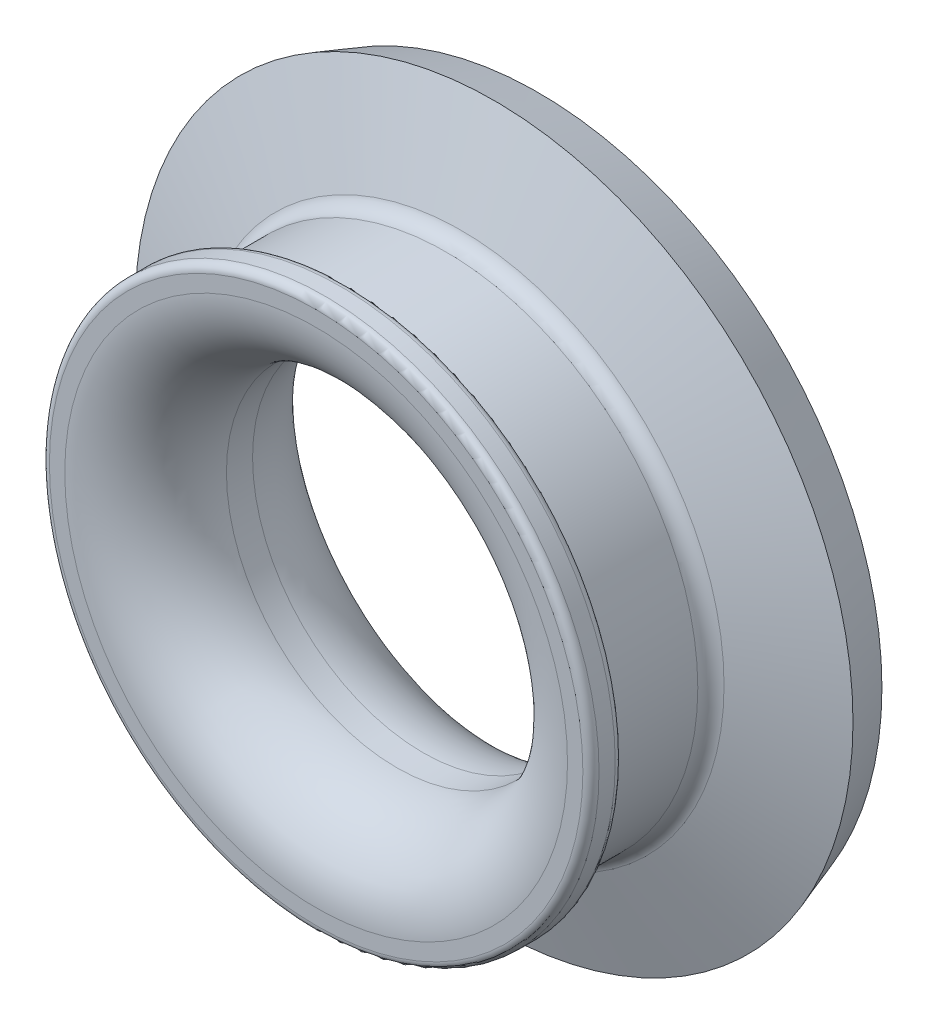
SolidWorks part; units mm, degrees
material "Nitrile Rubber"
ref_plane "Front Plane" through (0, 0, 0) normal (0, 0, 1) x (1, 0, 0)
ref_plane "Top Plane" through (0, 0, 0) normal (0, 1, 0) x (1, 0, 0)
ref_plane "Right Plane" through (0, 0, 0) normal (1, 0, 0) x (0, 0, -1)
sketch "Sketch1" plane through (0, 0, 0) normal (1, 0, 0) x (0, 0, -1)
  line L0 (0, 0) -> (95.2987, 0) construction
  line L1 (0, 33) -> (0, 31.1)
  line L2 (10, 21.1) -> (13.2339, 21.1)
  line L3 (24.9717, 30.6051) -> (27.5, 42.5)
  line L4 (27.5, 42.5) -> (22.02, 44.4)
  line L5 (22.02, 44.4) -> (17.962, 32.5043)
  line L6 (16.0691, 31.15) -> (5, 31.15)
  line L7 (4, 32.15) -> (4, 33)
  line L8 (3, 34) -> (1, 34)
  line L9 (27.5, 42.5) -> (27.5, 9.9557) construction
  arc A0 (4, 33) -> (3, 34) centre (3, 33) ccw
  arc A1 (1, 34) -> (0, 33) centre (1, 33) ccw
  arc A2 (5, 31.15) -> (4, 32.15) centre (5, 32.15) cw
  arc A3 (17.962, 32.5043) -> (16.0691, 31.15) centre (16.0691, 33.15) cw
  arc A4 (13.2339, 21.1) -> (24.9717, 30.6051) centre (13.2339, 33.1) ccw
  arc A5 (0, 31.1) -> (10, 21.1) centre (10, 31.1) ccw
  point P19 (17.5, 31.15)
  point P22 (22.9513, 21.1)
  dimension "D10" = 1
  dimension "D11" = 1
  dimension "D12" = 2
  dimension "D13" = 12
  dimension "D14" = 10
  dimension "D1" = 68
  dimension "D2" = 62.3
  dimension "D3" = 42.2
  dimension "D4" = 27.5
  dimension "D5" = 88.8
  dimension "D6" = 5.8
  dimension "D7" = 13.5
  dimension "D8" = 12
  dimension "D9" = 4
  dimension "D15" = 85
revolve "Revolve1" add sketch "Sketch1" angle 360 about L0
